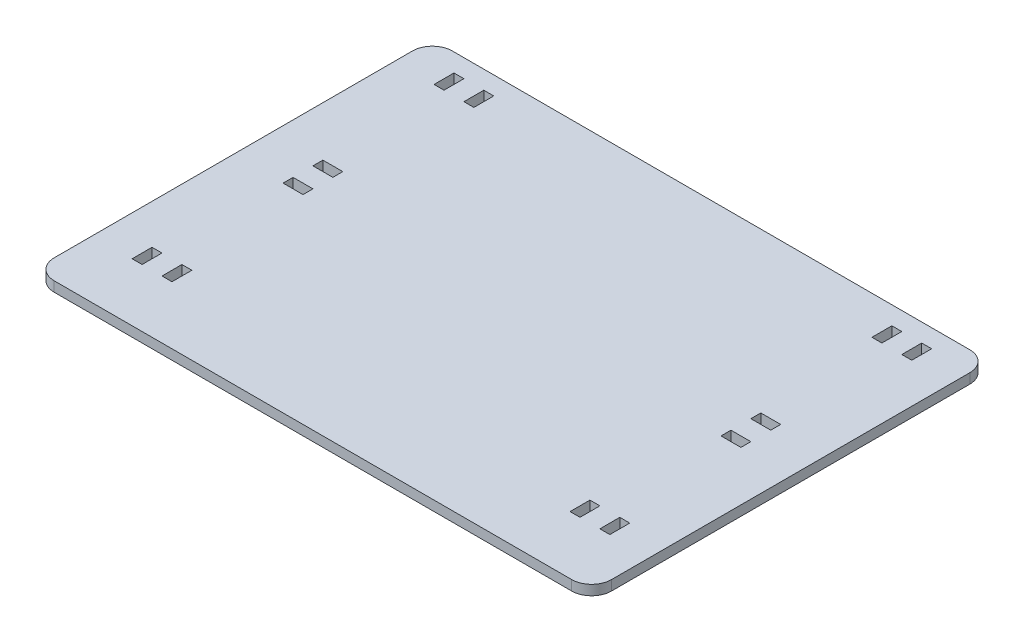
SolidWorks part; units mm, degrees
material "Pin"
ref_plane "Front" through (0, 0, 0) normal (0, 0, 1) x (1, 0, 0)
ref_plane "Top" through (0, 0, 0) normal (0, 1, 0) x (1, 0, 0)
ref_plane "Right" through (0, 0, 0) normal (1, 0, 0) x (0, 0, -1)
sketch "Esquisse2" plane through (0, 0, 0) normal (0, 1, 0) x (1, 0, 0)
  line L1 (-177.8, 127) -> (177.8, 127)
  line L2 (-177.8, 127) -> (-177.8, -127)
  line L3 (-177.8, -127) -> (177.8, -127)
  line L4 (177.8, 127) -> (177.8, -127)
  line L5 (-177.8, 127) -> (177.8, -127) construction
  line L6 (-177.8, -127) -> (177.8, 127) construction
  point P0 (0, 0)
  dimension "D1" = 355.6
  dimension "D2" = 254
extrude "Boss.-Extru.1" add sketch "Esquisse2" along normal blind 6.35
sketch "Esquisse3" plane through (0, 6.35, 0) normal (0, 1, 0) x (1, 0, 0)
  line L0 (-177.8, 127) -> (-177.8, -127) construction
  line L17 (-146.05, 25.4) -> (-133.35, 25.4)
  line L18 (-146.05, 25.4) -> (-146.05, 19.05)
  line L19 (-146.05, 19.05) -> (-133.35, 19.05)
  line L20 (-133.35, 25.4) -> (-133.35, 19.05)
  line L21 (-146.05, 25.4) -> (-133.35, 19.05) construction
  line L22 (-146.05, 19.05) -> (-133.35, 25.4) construction
  line L27 (0, 12.7) -> (-177.8, 12.7) construction
  line L28 (-146.05, 6.35) -> (-133.35, 6.35)
  line L30 (-133.35, -77.2668) -> (-127, -89.9668) construction
  line L31 (-133.35, -89.9668) -> (-127, -77.2668) construction
  line L32 (-152.4, -77.2668) -> (-146.05, -89.9668) construction
  line L33 (-152.4, -89.9668) -> (-146.05, -77.2668) construction
  line L42 (-146.05, 6.35) -> (-146.05, 0)
  line L43 (-146.05, 0) -> (-133.35, 0)
  line L44 (-133.35, 6.35) -> (-133.35, 0)
  line L45 (-146.05, 6.35) -> (-133.35, 0) construction
  line L46 (-146.05, 0) -> (-133.35, 6.35) construction
  line L47 (-127, -89.9668) -> (-127, -77.2668)
  line L48 (-152.4, 115.3668) -> (-146.05, 115.3668)
  line L49 (-152.4, 115.3668) -> (-152.4, 102.6668)
  line L50 (-152.4, 102.6668) -> (-146.05, 102.6668)
  line L51 (-146.05, 115.3668) -> (-146.05, 102.6668)
  line L52 (-152.4, 115.3668) -> (-146.05, 102.6668) construction
  line L53 (-152.4, 102.6668) -> (-146.05, 115.3668) construction
  line L54 (-133.35, 115.3668) -> (-127, 115.3668)
  line L55 (-133.35, 115.3668) -> (-133.35, 102.6668)
  line L56 (-133.35, 102.6668) -> (-127, 102.6668)
  line L57 (-127, 115.3668) -> (-127, 102.6668)
  line L58 (-133.35, 115.3668) -> (-127, 102.6668) construction
  line L59 (-133.35, 102.6668) -> (-127, 115.3668) construction
  line L60 (-133.35, -77.2668) -> (-127, -77.2668)
  line L61 (-133.35, -89.9668) -> (-133.35, -77.2668)
  line L62 (-133.35, -89.9668) -> (-127, -89.9668)
  line L63 (-146.05, -89.9668) -> (-146.05, -77.2668)
  line L64 (-152.4, -77.2668) -> (-146.05, -77.2668)
  line L65 (-152.4, -89.9668) -> (-152.4, -77.2668)
  line L66 (-152.4, -89.9668) -> (-146.05, -89.9668)
  line L67 (0, -50) -> (0, 50) construction
  line L68 (133.35, 102.6668) -> (127, 115.3668) construction
  line L69 (133.35, 115.3668) -> (127, 102.6668) construction
  line L70 (152.4, 102.6668) -> (146.05, 115.3668) construction
  line L71 (152.4, 115.3668) -> (146.05, 102.6668) construction
  line L72 (146.05, 0) -> (133.35, 6.35) construction
  line L73 (146.05, 6.35) -> (133.35, 0) construction
  line L74 (152.4, -89.9668) -> (146.05, -77.2668) construction
  line L75 (152.4, -77.2668) -> (146.05, -89.9668) construction
  line L76 (133.35, -89.9668) -> (127, -77.2668) construction
  line L77 (133.35, -77.2668) -> (127, -89.9668) construction
  line L78 (146.05, 19.05) -> (133.35, 25.4) construction
  line L79 (146.05, 25.4) -> (133.35, 19.05) construction
  line L80 (152.4, -89.9668) -> (146.05, -89.9668)
  line L81 (152.4, -89.9668) -> (152.4, -77.2668)
  line L82 (152.4, -77.2668) -> (146.05, -77.2668)
  line L83 (146.05, -89.9668) -> (146.05, -77.2668)
  line L84 (133.35, -89.9668) -> (127, -89.9668)
  line L85 (133.35, -89.9668) -> (133.35, -77.2668)
  line L86 (133.35, -77.2668) -> (127, -77.2668)
  line L87 (127, 115.3668) -> (127, 102.6668)
  line L88 (133.35, 102.6668) -> (127, 102.6668)
  line L89 (133.35, 115.3668) -> (133.35, 102.6668)
  line L90 (133.35, 115.3668) -> (127, 115.3668)
  line L91 (146.05, 115.3668) -> (146.05, 102.6668)
  line L92 (152.4, 102.6668) -> (146.05, 102.6668)
  line L93 (152.4, 115.3668) -> (152.4, 102.6668)
  line L94 (152.4, 115.3668) -> (146.05, 115.3668)
  line L95 (127, -89.9668) -> (127, -77.2668)
  line L96 (133.35, 6.35) -> (133.35, 0)
  line L97 (146.05, 0) -> (133.35, 0)
  line L98 (146.05, 6.35) -> (146.05, 0)
  line L99 (146.05, 6.35) -> (133.35, 6.35)
  line L100 (133.35, 25.4) -> (133.35, 19.05)
  line L101 (146.05, 19.05) -> (133.35, 19.05)
  line L102 (146.05, 25.4) -> (146.05, 19.05)
  line L103 (146.05, 25.4) -> (133.35, 25.4)
  line L104 (177.8, 127) -> (-177.8, 127) construction
  point P0 (-139.7, 22.225)
  point P5 (-139.7, 3.175)
  point P20 (-130.175, -83.6168)
  point P21 (-149.225, -83.6168)
  point P27 (-149.225, 109.0168)
  point P33 (-130.175, 109.0168)
  point P62 (130.175, 109.0168)
  point P63 (149.225, 109.0168)
  point P64 (149.225, -83.6168)
  point P65 (130.175, -83.6168)
  point P66 (139.7, 3.175)
  point P67 (139.7, 22.225)
  dimension "D1" = 6.35
  dimension "D2" = 12.7
  dimension "D3" = 12.7
  dimension "D4" = 6.35
  dimension "D5" = 12.7
  dimension "D6" = 31.75
  dimension "D7" = 6.35
  dimension "D8" = 12.7
  dimension "D9" = 6.35
  dimension "D10" = 12.7
  dimension "D11" = 6.35
  dimension "D12" = 12.7
  dimension "D13" = 25.4
  dimension "D14" = 77.2668
  dimension "D15" = 114.3
extrude "Enlèv. mat.-Extru.1" cut sketch "Esquisse3" against normal through all and the other way through all
fillet "Congé1" radius 12.7 4 edges at (-177.8, 3.175, 127) (177.8, 3.175, 127) (177.8, 3.175, -127) (-177.8, 3.175, -127)
